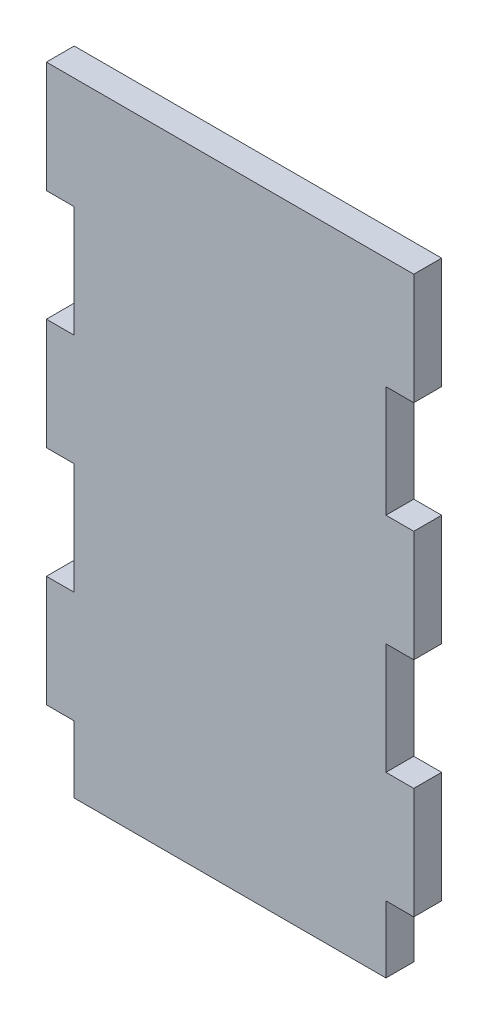
SolidWorks part; units mm, degrees
ref_plane "Front Plane" through (0, 0, 0) normal (0, 0, 1) x (1, 0, 0)
ref_plane "Top Plane" through (0, 0, 0) normal (0, 1, 0) x (1, 0, 0)
ref_plane "Right Plane" through (0, 0, 0) normal (1, 0, 0) x (0, 0, -1)
sketch "Sketch1" plane through (0, 0, 0) normal (0, 0, 1) x (1, 0, 0)
  line L0 (-35.56, 45.72) -> (-41.91, 45.72)
  line L1 (-35.56, 71.12) -> (35.56, 71.12)
  line L2 (-35.56, 71.12) -> (-35.56, -71.12)
  line L3 (-35.56, -71.12) -> (35.56, -71.12)
  line L4 (35.56, 71.12) -> (35.56, -71.12)
  line L5 (-35.56, 71.12) -> (-41.91, 71.12)
  line L6 (-35.56, 71.12) -> (-35.56, -71.12)
  line L7 (-35.56, -71.12) -> (-41.91, -71.12)
  line L8 (-41.91, 71.12) -> (-41.91, -71.12)
  line L9 (35.56, 71.12) -> (41.91, 71.12)
  line L10 (35.56, 71.12) -> (35.56, -71.12)
  line L11 (35.56, -71.12) -> (41.91, -71.12)
  line L12 (41.91, 71.12) -> (41.91, -71.12)
  line L13 (35.56, 45.72) -> (41.91, 45.72)
  line L14 (-35.56, 20.32) -> (-41.91, 20.32)
  line L15 (35.56, 20.32) -> (41.91, 20.32)
  line L16 (-35.56, -5.08) -> (-41.91, -5.08)
  line L17 (35.56, -5.08) -> (41.91, -5.08)
  line L18 (-35.56, -30.48) -> (-41.91, -30.48)
  line L19 (35.56, -30.48) -> (41.91, -30.48)
  line L20 (-35.56, -55.88) -> (-41.91, -55.88)
  line L21 (35.56, -55.88) -> (41.91, -55.88)
  line L22 (-35.56, 71.12) -> (-35.56, 45.72) construction
  point P4 (0, 71.12)
  point P6 (-35.56, 0)
  dimension "D1" = 71.12
  dimension "D2" = 142.24
  dimension "D3" = 6.35
  dimension "D4" = 6.35
  dimension "D6" = 25.4
  dimension "D5" = 6
extrude "Boss-Extrude1" add sketch "Sketch1" along normal blind 6.35 contours L4 L1 L2 L6 L3 L10 | L5 L8 L0 L2 | L16 L6 L14 L8 | L20 L6 L18 L8 | L4 L21 L12 L19 | L4 L17 L12 L15 | L4 L13 L12 L9
